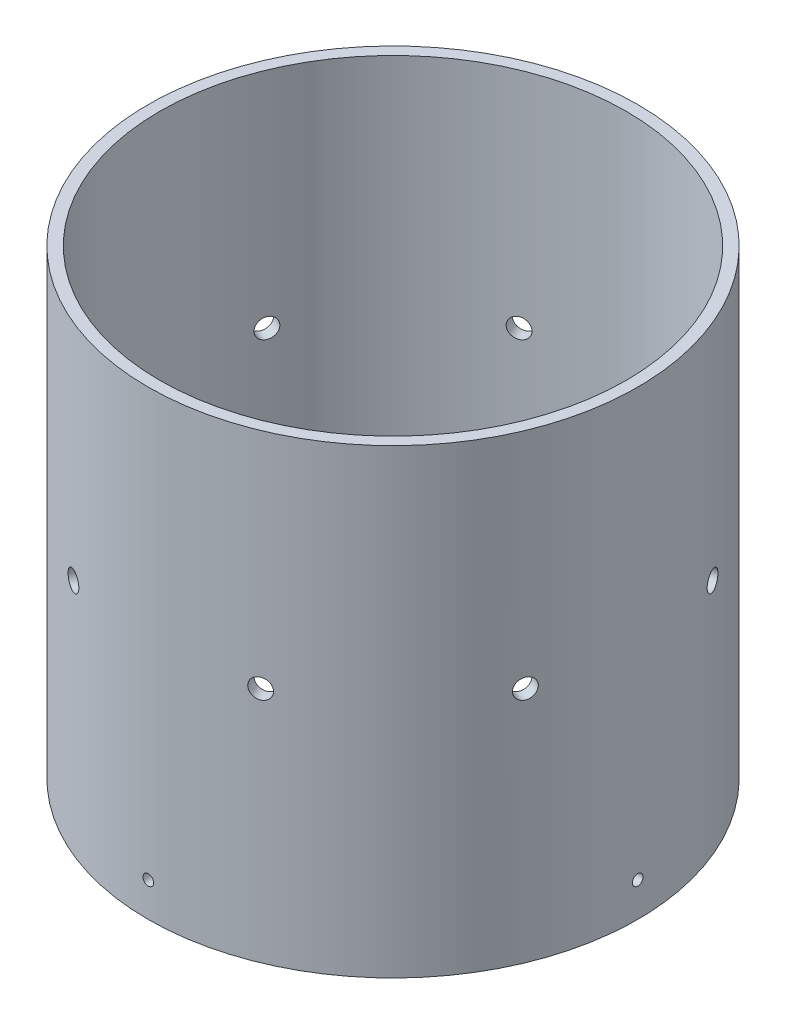
SolidWorks part; units mm, degrees
material "Corrugated Paper"
ref_plane "Front Plane" through (0, 0, 0) normal (0, 0, 1) x (1, 0, 0)
ref_plane "Top Plane" through (0, 0, 0) normal (0, 1, 0) x (1, 0, 0)
ref_plane "Right Plane" through (0, 0, 0) normal (1, 0, 0) x (0, 0, -1)
sketch "Sketch1" plane through (0, 0, 0) normal (0, 1, 0) x (1, 0, 0)
  circle A0 centre (0, 0) radius 55.626
  circle A1 centre (0, 0) radius 52.9844
  dimension "D1" = 111.252
  dimension "D2" = 105.9688
extrude "Boss-Extrude1" add sketch "Sketch1" along normal blind 104.775 from offset 352.425
ref_plane "Plane1" through (0, 0, 55.626) normal (0, 0, 1) x (1, 0, 0)
hole_wizard "#2 Clearance Hole1" positions "Sketch3" profile "Sketch4" hole size "#2" standard "ANSI Inch"
sketch "Sketch3" plane through (0, 0, 55.626) normal (0, 0, 1) x (1, 0, 0)
  line L0 (55.626, 457.2) -> (-55.626, 457.2) construction
  point P0 (0, 360.2228)
  dimension "D1" = 96.9772
sketch "Sketch4" plane through (0, 360.2228, 55.626) normal (1, 0, 0) x (0, -1, 0)
  line L0 (0, 0) -> (0, 55.5966)
  line L1 (0, 55.5966) -> (1.2192, 54.864)
  line L2 (1.2192, 54.864) -> (1.2192, 0)
  line L5 (1.2192, 0) -> (0, 0)
  line L10 (0, 55.5966) -> (-1.2192, 54.864) construction
  line L11 (0, -6.35) -> (0, 107.95) construction
  dimension "Hole Dia." = 2.4384
  dimension "Hole Depth" = 54.864
  dimension "Drill Angle" = 118
ref_plane "Plane2" through (21.2871, 0, 51.3917) normal (0.3827, 0, 0.9239) x (0, -1, 0)
hole_wizard "#8 Clearance Hole1" positions "Sketch5" profile "Sketch6" hole size "#8" standard "ANSI Inch"
sketch "Sketch5" plane through (21.2871, 0, 51.3917) normal (0.3827, 0, 0.9239) x (0, -1, 0)
  line L0 (-457.2, 55.626) -> (-457.2, -55.626) construction
  point P0 (-406.4, 0)
  dimension "D1" = 50.8
sketch "Sketch6" plane through (21.2871, 406.4, 51.3917) normal (0, 1, 0) x (0.9239, 0, -0.3827)
  line L0 (0, 0) -> (0, 56.2147)
  line L1 (0, 56.2147) -> (2.2479, 54.864)
  line L2 (2.2479, 54.864) -> (2.2479, 0)
  line L5 (2.2479, 0) -> (0, 0)
  line L10 (0, 56.2147) -> (-2.2479, 54.864) construction
  line L11 (0, -6.35) -> (0, 107.95) construction
  dimension "Hole Dia." = 4.4958
  dimension "Hole Depth" = 54.864
  dimension "Drill Angle" = 118
pattern_circular "CirPattern1" count 4 over 360 about axis through (0, 457.2, 0) along (0, -1, 0) of "#2 Clearance Hole1"
pattern_circular "CirPattern2" count 8 over 360 about axis through (0, 457.2, 0) along (0, -1, 0) of "#8 Clearance Hole1"
